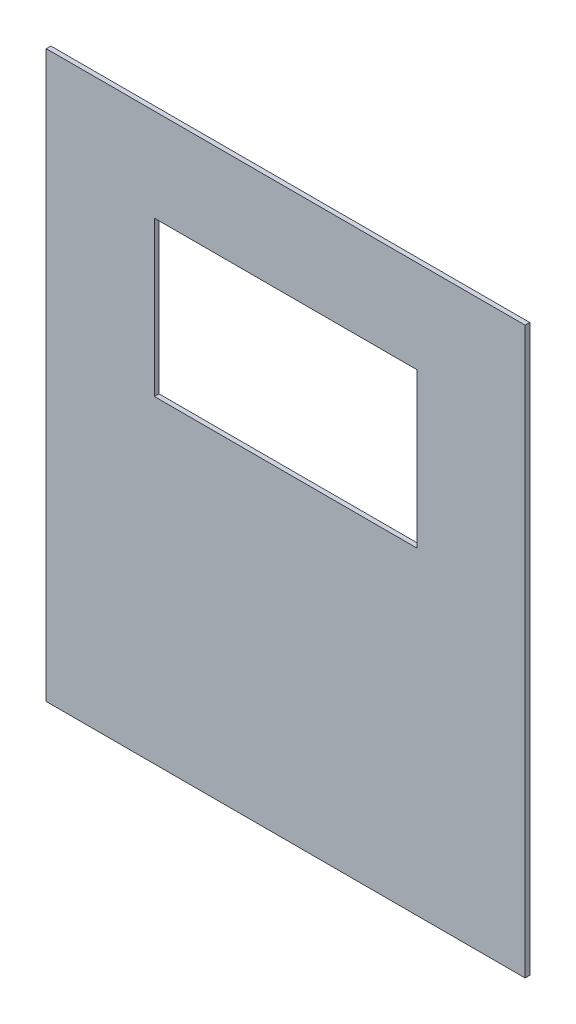
SolidWorks part; units mm, degrees
ref_plane "前视基准面" through (0, 0, 0) normal (0, 0, 1) x (1, 0, 0)
ref_plane "上视基准面" through (0, 0, 0) normal (0, 1, 0) x (1, 0, 0)
ref_plane "右视基准面" through (0, 0, 0) normal (1, 0, 0) x (0, 0, -1)
other "Configuration Table"
sketch "草图1" plane through (0, 0, 0) normal (0, 0, 1) x (1, 0, 0)
  line L1 (0, 0) -> (310, 0)
  line L2 (0, 0) -> (0, 366)
  line L3 (0, 366) -> (310, 366)
  line L4 (310, 0) -> (310, 366)
  line L5 (240, 306) -> (70, 306)
  line L6 (240, 306) -> (240, 206)
  line L7 (240, 206) -> (70, 206)
  line L8 (70, 306) -> (70, 206)
  point P9 (240, 256)
  dimension "D1" = 310
  dimension "D2" = 366
  dimension "D3" = 100
  dimension "D4" = 170
  dimension "D5" = 70
  dimension "D6" = 60
extrude "凸台-拉伸1" add sketch "草图1" along normal blind 3
